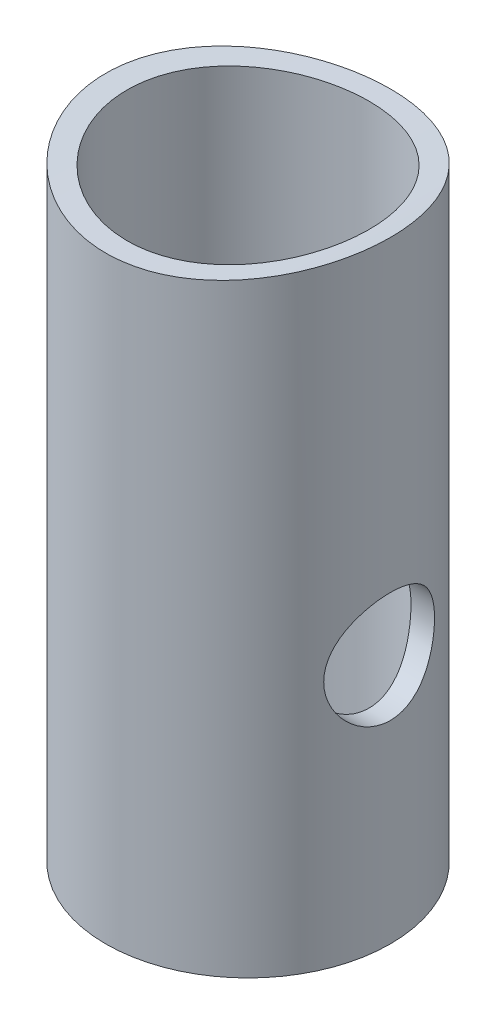
SolidWorks part; units mm, degrees
ref_plane "Front Plane" through (0, 0, 0) normal (0, 0, 1) x (1, 0, 0)
ref_plane "Top Plane" through (0, 0, 0) normal (0, 1, 0) x (1, 0, 0)
ref_plane "Right Plane" through (0, 0, 0) normal (1, 0, 0) x (0, 0, -1)
sketch "Sketch1" plane through (0, 0, 0) normal (0, 1, 0) x (1, 0, 0)
  circle A0 centre (0, 0) radius 57.15
  circle A1 centre (0, 0) radius 48.59
  dimension "D1" = 114.3
  dimension "D2" = 8.56
extrude "Boss-Extrude1" add sketch "Sketch1" along normal blind 245.75
sketch "Sketch2" plane through (0, 0, 0) normal (0, 0, 1) x (1, 0, 0)
  line L1 (57.15, 245.75) -> (-57.15, 245.75) construction
  line L2 (57.15, 245.75) -> (-57.15, 245.75)
  arc A0 (-57.15, 245.75) -> (57.15, 245.75) centre (0, 543.5615) ccw
  dimension "D1" = 606.4909
extrude "Cut-Extrude1" cut sketch "Sketch2" against normal through all both and the other way through all
sketch "Sketch3" plane through (0, 0, 0) normal (1, 0, 0) x (0, 0, -1)
  circle A0 centre (0, 100) radius 22.25
  dimension "D1" = 44.5
  dimension "D2" = 100
extrude "Cut-Extrude2" cut sketch "Sketch3" along normal blind 111
